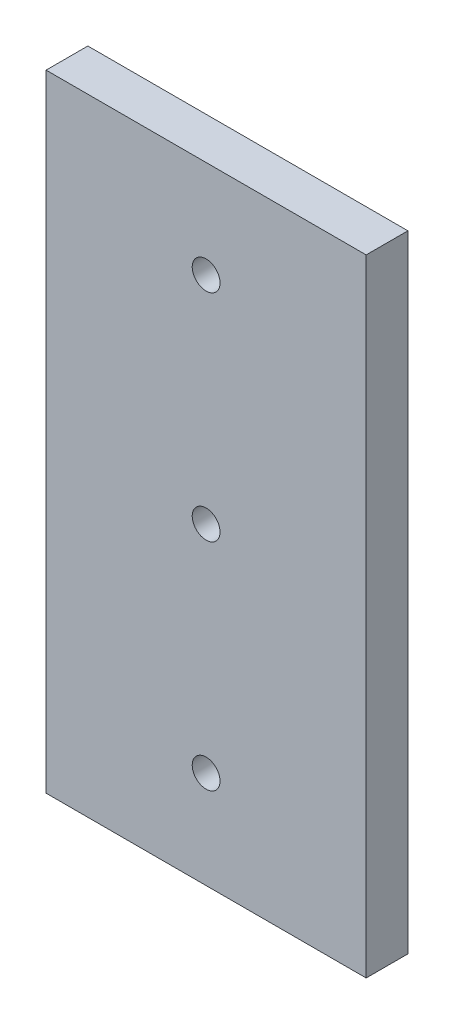
SolidWorks part; units mm, degrees
material "Porcelana cerâmica"
ref_plane "Plano frontal" through (0, 0, 0) normal (0, 0, 1) x (1, 0, 0)
ref_plane "Plano superior" through (0, 0, 0) normal (0, 1, 0) x (1, 0, 0)
ref_plane "Plano direito" through (0, 0, 0) normal (1, 0, 0) x (0, 0, -1)
sketch "Esboço1" plane through (0, 0, 0) normal (0, 0, 1) x (1, 0, 0)
  line L1 (0, 0) -> (115, 0)
  line L2 (0, 0) -> (0, 225)
  line L3 (0, 225) -> (115, 225)
  line L4 (115, 0) -> (115, 225)
  dimension "D1" = 115
  dimension "D2" = 225
extrude "Ressalto-extrusão1" add sketch "Esboço1" along normal blind 15
sketch "Esboço2" plane through (0, 0, 15) normal (0, 0, 1) x (1, 0, 0)
  line L0 (57.5, 225) -> (57.5, 0) construction
  line L1 (115, 225) -> (0, 225) construction
  line L2 (0, 0) -> (115, 0) construction
  line L3 (57.5, 112.5) -> (115, 112.5) construction
  line L4 (115, 0) -> (115, 225) construction
  line L5 (0, 190) -> (115, 190) construction
  line L7 (0, 225) -> (0, 0) construction
  circle A0 centre (57.5, 190) radius 5
  circle A1 centre (57.5, 112.5) radius 5
  circle A2 centre (57.5, 35) radius 5
  dimension "D1" = 10
  dimension "D2" = 10
  dimension "D3" = 77.5
  dimension "D5" = 35
extrude "Corte-extrusão1" cut sketch "Esboço2" against normal through all
